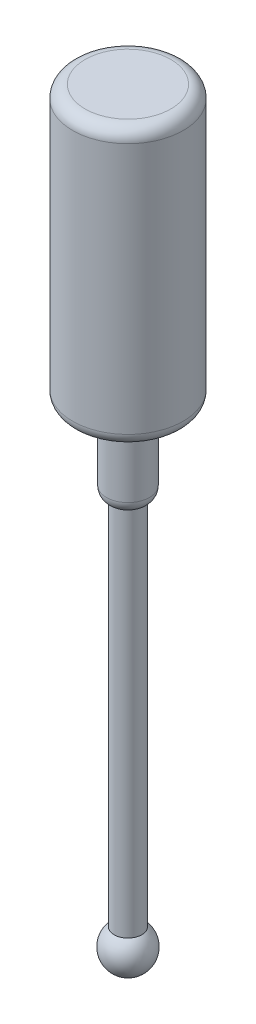
SolidWorks part; units mm, degrees
ref_plane "Płaszczyzna przednia" through (0, 0, 0) normal (0, 0, 1) x (1, 0, 0)
ref_plane "Płaszczyzna górna" through (0, 0, 0) normal (0, 1, 0) x (1, 0, 0)
ref_plane "Płaszczyzna prawa" through (0, 0, 0) normal (1, 0, 0) x (0, 0, -1)
sketch "Szkic1" plane through (0, 0, 0) normal (0, 0, 1) x (1, 0, 0)
  line L0 (0, 8) -> (0, -8)
  arc A0 (0, 8) -> (0, -8) centre (0, 0) cw
  dimension "D1" = 8
revolve "Obrót1" add sketch "Szkic1" angle 360 about L0
sketch "Szkic2" plane through (0, 0, 0) normal (0, 1, 0) x (1, 0, 0)
  circle A0 centre (0, 0) radius 5
  dimension "D1" = 10
extrude "Dodanie-wyciągnięcie1" add sketch "Szkic2" along normal blind 270
sketch "Szkic3" plane through (0, 0, 0) normal (0, 0, 1) x (1, 0, 0)
  line L0 (0, 270) -> (-15.5, 270)
  line L1 (5, 270) -> (-5, 270) construction
  line L2 (-20, 265.5) -> (-20, 174.5)
  line L3 (-7.75, 165.5) -> (-7.75, 144.5)
  line L4 (-3.25, 140) -> (0, 140)
  line L5 (-15.5, 170) -> (-12.25, 170)
  line L6 (0, 270) -> (0, 140)
  arc A0 (-15.5, 270) -> (-20, 265.5) centre (-15.5, 265.5) ccw
  arc A1 (-7.75, 144.5) -> (-3.25, 140) centre (-3.25, 144.5) ccw
  arc A2 (-20, 174.5) -> (-15.5, 170) centre (-15.5, 174.5) ccw
  arc A3 (-7.75, 165.5) -> (-12.25, 170) centre (-12.25, 165.5) ccw
  point P4 (0, 0)
  point P9 (-7.75, 270)
  point P12 (-20, 270)
  point P17 (-20, 170)
  point P20 (-7.75, 170)
  dimension "D4" = 4.5
  dimension "D1" = 130
  dimension "D2" = 100
  dimension "D3" = 20
revolve "Obrót2" add sketch "Szkic3" angle 360 about L6
